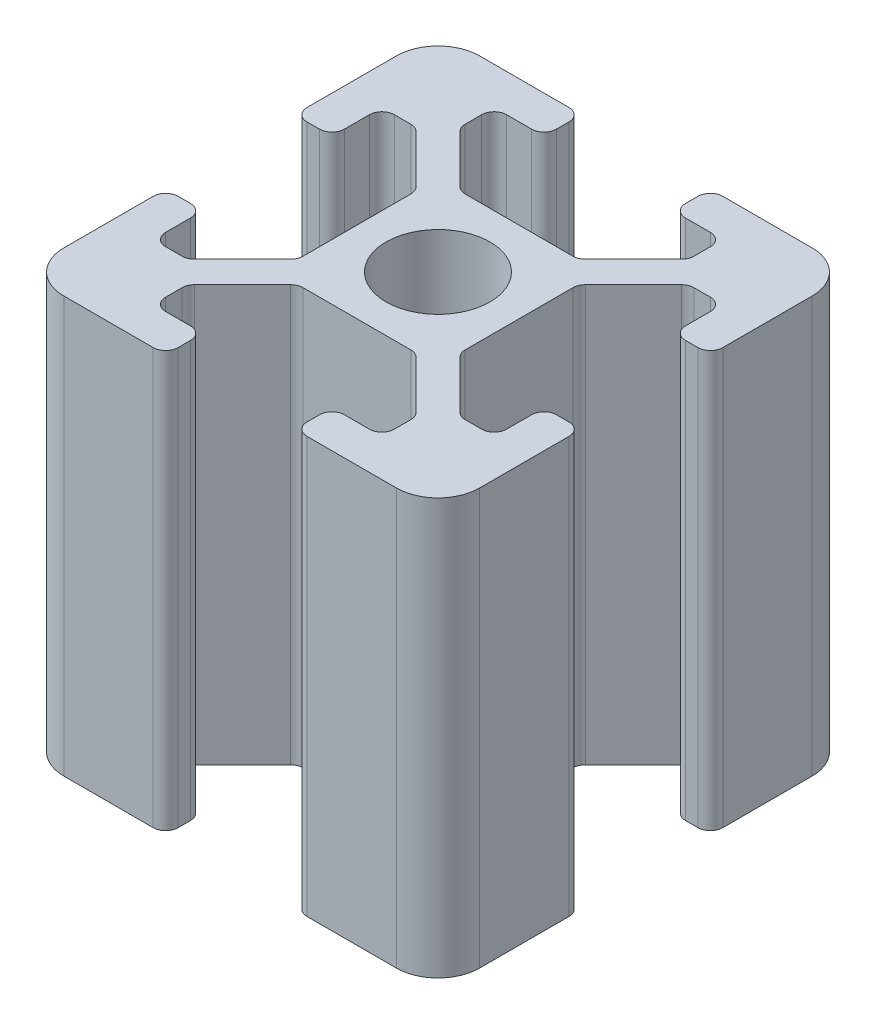
SolidWorks part; units mm, degrees
ref_plane "前视基准面" through (0, 0, 0) normal (0, 0, 1) x (1, 0, 0)
ref_plane "上视基准面" through (0, 0, 0) normal (0, 1, 0) x (1, 0, 0)
ref_plane "右视基准面" through (0, 0, 0) normal (1, 0, 0) x (0, 0, -1)
sketch "草图1" plane through (0, 0, 0) normal (0, 1, 0) x (1, 0, 0)
  line L0 (3.1, 8.8) -> (3.1, 9.4)
  line L1 (-10, -10) -> (10, -10) construction
  line L2 (-10, -10) -> (-10, 10) construction
  line L3 (-10, 10) -> (10, 10) construction
  line L4 (10, -10) -> (10, 10) construction
  line L5 (-10, -10) -> (10, 10) construction
  line L6 (-10, 10) -> (10, -10) construction
  line L7 (3.7, 10) -> (8, 10)
  line L8 (0, 10) -> (0, -10) construction
  line L9 (3.7, 8.2) -> (4.9, 8.2)
  line L10 (5.3243, 6.3849) -> (3.0151, 4.0757)
  line L11 (2.5908, 3.9) -> (0, 3.9)
  line L12 (5.5, 7.6) -> (5.5, 6.8092)
  line L13 (10, 3.7) -> (10, 8)
  line L14 (8.8, 3.1) -> (9.4, 3.1)
  line L15 (8.2, 3.7) -> (8.2, 4.9)
  line L16 (7.6, 5.5) -> (6.8092, 5.5)
  line L17 (6.3849, 5.3243) -> (4.0757, 3.0151)
  line L18 (3.9, 2.5908) -> (3.9, 0)
  line L19 (3.9, -2.5908) -> (3.9, 0)
  line L20 (2.5908, -3.9) -> (0, -3.9)
  line L21 (5.3243, -6.3849) -> (3.0151, -4.0757)
  line L22 (6.3849, -5.3243) -> (4.0757, -3.0151)
  line L23 (5.5, -7.6) -> (5.5, -6.8092)
  line L24 (3.7, -8.2) -> (4.9, -8.2)
  line L25 (3.1, -8.8) -> (3.1, -9.4)
  line L26 (3.7, -10) -> (8, -10)
  line L27 (10, -3.7) -> (10, -8)
  line L28 (8.8, -3.1) -> (9.4, -3.1)
  line L29 (8.2, -3.7) -> (8.2, -4.9)
  line L30 (7.6, -5.5) -> (6.8092, -5.5)
  line L31 (-2.5908, -3.9) -> (0, -3.9)
  line L32 (-3.9, -2.5908) -> (-3.9, 0)
  line L33 (-6.3849, -5.3243) -> (-4.0757, -3.0151)
  line L34 (-5.3243, -6.3849) -> (-3.0151, -4.0757)
  line L35 (-7.6, -5.5) -> (-6.8092, -5.5)
  line L36 (-8.2, -3.7) -> (-8.2, -4.9)
  line L37 (-8.8, -3.1) -> (-9.4, -3.1)
  line L38 (-10, -3.7) -> (-10, -8)
  line L39 (-3.7, -10) -> (-8, -10)
  line L40 (-3.1, -8.8) -> (-3.1, -9.4)
  line L41 (-3.7, -8.2) -> (-4.9, -8.2)
  line L42 (-5.5, -7.6) -> (-5.5, -6.8092)
  line L43 (-3.9, 2.5908) -> (-3.9, 0)
  line L44 (-2.5908, 3.9) -> (0, 3.9)
  line L45 (-5.3243, 6.3849) -> (-3.0151, 4.0757)
  line L46 (-6.3849, 5.3243) -> (-4.0757, 3.0151)
  line L47 (-5.5, 7.6) -> (-5.5, 6.8092)
  line L48 (-3.7, 8.2) -> (-4.9, 8.2)
  line L49 (-3.1, 8.8) -> (-3.1, 9.4)
  line L50 (-3.7, 10) -> (-8, 10)
  line L51 (-10, 3.7) -> (-10, 8)
  line L52 (-8.8, 3.1) -> (-9.4, 3.1)
  line L53 (-8.2, 3.7) -> (-8.2, 4.9)
  line L54 (-7.6, 5.5) -> (-6.8092, 5.5)
  circle A0 centre (0, 0) radius 2.5
  arc A1 (3.0151, 4.0757) -> (2.5908, 3.9) centre (2.5908, 4.5) cw
  arc A2 (5.5, 6.8092) -> (5.3243, 6.3849) centre (4.9, 6.8092) cw
  arc A3 (5.5, 7.6) -> (4.9, 8.2) centre (4.9, 7.6) ccw
  arc A4 (3.1, 8.8) -> (3.7, 8.2) centre (3.7, 8.8) ccw
  arc A5 (3.7, 10) -> (3.1, 9.4) centre (3.7, 9.4) ccw
  arc A6 (10, 3.7) -> (9.4, 3.1) centre (9.4, 3.7) cw
  arc A7 (8.8, 3.1) -> (8.2, 3.7) centre (8.8, 3.7) cw
  arc A8 (7.6, 5.5) -> (8.2, 4.9) centre (7.6, 4.9) cw
  arc A9 (6.8092, 5.5) -> (6.3849, 5.3243) centre (6.8092, 4.9) ccw
  arc A10 (4.0757, 3.0151) -> (3.9, 2.5908) centre (4.5, 2.5908) ccw
  arc A11 (10, 8) -> (8, 10) centre (8, 8) ccw
  arc A12 (3.0151, -4.0757) -> (2.5908, -3.9) centre (2.5908, -4.5) ccw
  arc A13 (4.0757, -3.0151) -> (3.9, -2.5908) centre (4.5, -2.5908) cw
  arc A14 (5.5, -6.8092) -> (5.3243, -6.3849) centre (4.9, -6.8092) ccw
  arc A15 (6.8092, -5.5) -> (6.3849, -5.3243) centre (6.8092, -4.9) cw
  arc A16 (5.5, -7.6) -> (4.9, -8.2) centre (4.9, -7.6) cw
  arc A17 (3.1, -8.8) -> (3.7, -8.2) centre (3.7, -8.8) cw
  arc A18 (3.7, -10) -> (3.1, -9.4) centre (3.7, -9.4) cw
  arc A19 (8, -10) -> (10, -8) centre (8, -8) ccw
  arc A20 (10, -3.7) -> (9.4, -3.1) centre (9.4, -3.7) ccw
  arc A21 (8.8, -3.1) -> (8.2, -3.7) centre (8.8, -3.7) ccw
  arc A22 (7.6, -5.5) -> (8.2, -4.9) centre (7.6, -4.9) ccw
  arc A23 (-4.0757, -3.0151) -> (-3.9, -2.5908) centre (-4.5, -2.5908) ccw
  arc A24 (-3.0151, -4.0757) -> (-2.5908, -3.9) centre (-2.5908, -4.5) cw
  arc A25 (-6.8092, -5.5) -> (-6.3849, -5.3243) centre (-6.8092, -4.9) ccw
  arc A26 (-5.5, -6.8092) -> (-5.3243, -6.3849) centre (-4.9, -6.8092) cw
  arc A27 (-7.6, -5.5) -> (-8.2, -4.9) centre (-7.6, -4.9) cw
  arc A28 (-8.8, -3.1) -> (-8.2, -3.7) centre (-8.8, -3.7) cw
  arc A29 (-10, -3.7) -> (-9.4, -3.1) centre (-9.4, -3.7) cw
  arc A30 (-10, -8) -> (-8, -10) centre (-8, -8) ccw
  arc A31 (-3.7, -10) -> (-3.1, -9.4) centre (-3.7, -9.4) ccw
  arc A32 (-3.1, -8.8) -> (-3.7, -8.2) centre (-3.7, -8.8) ccw
  arc A33 (-5.5, -7.6) -> (-4.9, -8.2) centre (-4.9, -7.6) ccw
  arc A34 (-3.0151, 4.0757) -> (-2.5908, 3.9) centre (-2.5908, 4.5) ccw
  arc A35 (-4.0757, 3.0151) -> (-3.9, 2.5908) centre (-4.5, 2.5908) cw
  arc A36 (-5.5, 6.8092) -> (-5.3243, 6.3849) centre (-4.9, 6.8092) ccw
  arc A37 (-6.8092, 5.5) -> (-6.3849, 5.3243) centre (-6.8092, 4.9) cw
  arc A38 (-5.5, 7.6) -> (-4.9, 8.2) centre (-4.9, 7.6) cw
  arc A39 (-3.1, 8.8) -> (-3.7, 8.2) centre (-3.7, 8.8) cw
  arc A40 (-3.7, 10) -> (-3.1, 9.4) centre (-3.7, 9.4) cw
  arc A41 (-8, 10) -> (-10, 8) centre (-8, 8) ccw
  arc A42 (-10, 3.7) -> (-9.4, 3.1) centre (-9.4, 3.7) ccw
  arc A43 (-8.8, 3.1) -> (-8.2, 3.7) centre (-8.8, 3.7) ccw
  arc A44 (-7.6, 5.5) -> (-8.2, 4.9) centre (-7.6, 4.9) ccw
  point P0 (0, 0)
  point P20 (5.5, 6.5607)
  point P25 (3.1, 8.2)
  point P28 (3.1, 10)
  point P156 (0, 0)
  dimension "D3" = 5
  dimension "D9" = 0.6
  dimension "D10" = 2
  dimension "D1" = 20
  dimension "D2" = 20
  dimension "D4" = 6.1
  dimension "D5" = 1.5
  dimension "D6" = 1.8
  dimension "D7" = 3.1
  dimension "D8" = 4.5
  dimension "D11" = 4
extrude "凸台-拉伸1" add sketch "草图1" along normal blind 20
